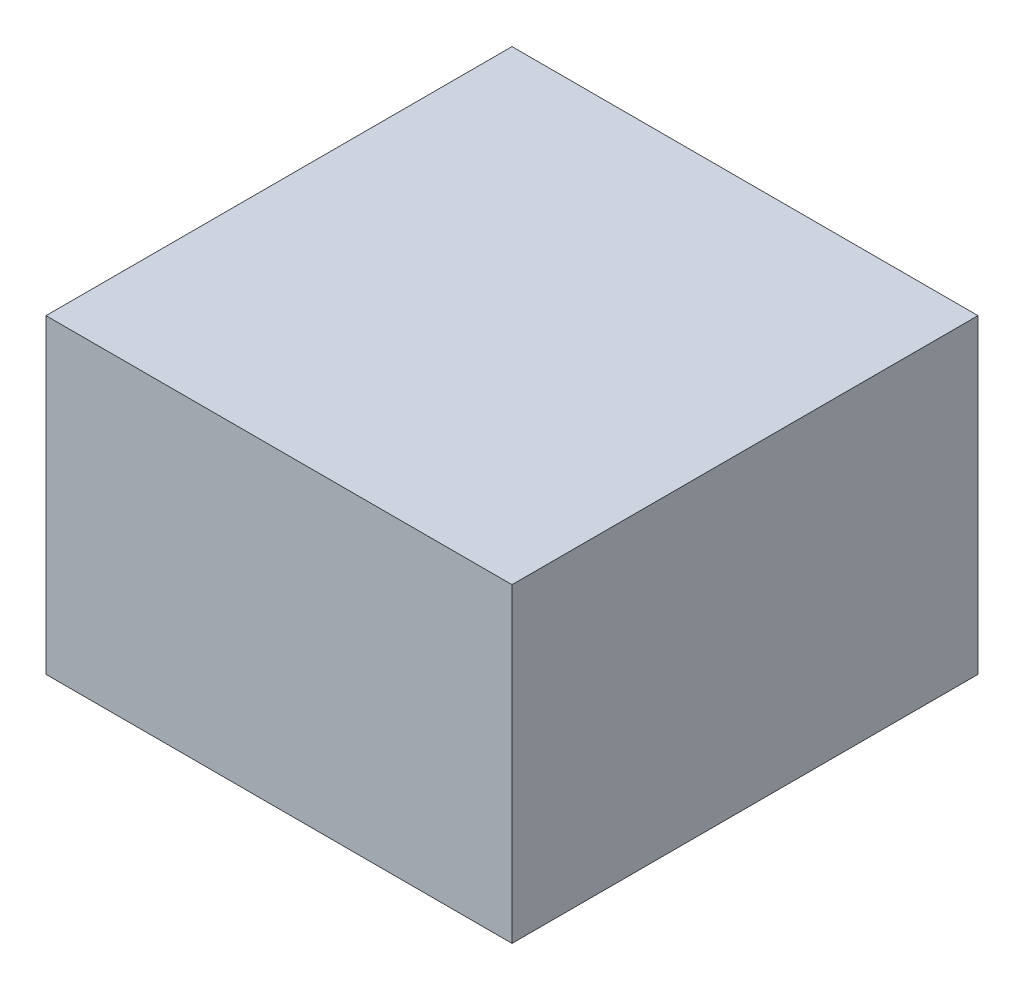
SolidWorks part; units mm, degrees
ref_plane "Front Plane" through (0, 0, 0) normal (0, 0, 1) x (1, 0, 0)
ref_plane "Top Plane" through (0, 0, 0) normal (0, 1, 0) x (1, 0, 0)
ref_plane "Right Plane" through (0, 0, 0) normal (1, 0, 0) x (0, 0, -1)
sketch "Sketch1" plane through (0, 0, 0) normal (0, 0, 1) x (1, 0, 0)
  line L1 (-30, -20) -> (30, -20)
  line L2 (-30, -20) -> (-30, 20)
  line L3 (-30, 20) -> (30, 20)
  line L4 (30, -20) -> (30, 20)
  line L5 (-30, -20) -> (30, 20) construction
  line L6 (-30, 20) -> (30, -20) construction
  point P0 (0, 0)
  dimension "D1" = 60
  dimension "D2" = 40
extrude "Boss-Extrude1" add sketch "Sketch1" along normal blind 60
sketch "Sketch2" plane through (0, 0, 0) normal (0, 0, -1) x (-1, 0, 0)
  line L0 (0, 20) -> (0, -20) construction
  line L1 (-30, 20) -> (30, 20) construction
  line L2 (30, -20) -> (-30, -20) construction
  line L3 (0, -20) -> (0, 0) construction
  line L4 (0, 0) -> (20.25, 0) construction
  line L6 (-20.25, -10) -> (20.25, -10)
  line L7 (-20.25, -10) -> (-20.25, 10)
  line L8 (-20.25, 10) -> (20.25, 10)
  line L9 (20.25, -10) -> (20.25, 10)
  line L10 (-20.25, -10) -> (20.25, 10) construction
  line L11 (-20.25, 10) -> (20.25, -10) construction
  dimension "D1" = 20.25
  dimension "D2" = 20
extrude "Cut-Extrude1" cut sketch "Sketch2" against normal blind 39
sketch "Sketch3" plane through (0, 0, 0) normal (0, 0, -1) x (-1, 0, 0)
  line L0 (0, 0) -> (30, 20) construction
  line L1 (30, 20) -> (30, -20) construction
  line L2 (0, 0) -> (0, 15.7289) construction
  line L3 (0, 15.7289) -> (11.9003, 0) construction
  line L4 (11.9003, 0) -> (-11.9003, 0) construction
  circle A0 centre (26, 17.3333) radius 2
  circle A1 centre (-26, 17.3333) radius 2
  circle A2 centre (26, -17.3333) radius 2
  circle A3 centre (-26, -17.3333) radius 2
  dimension "D1" = 4
  dimension "D2" = 4
extrude "Cut-Extrude2" cut sketch "Sketch3" against normal blind 5
